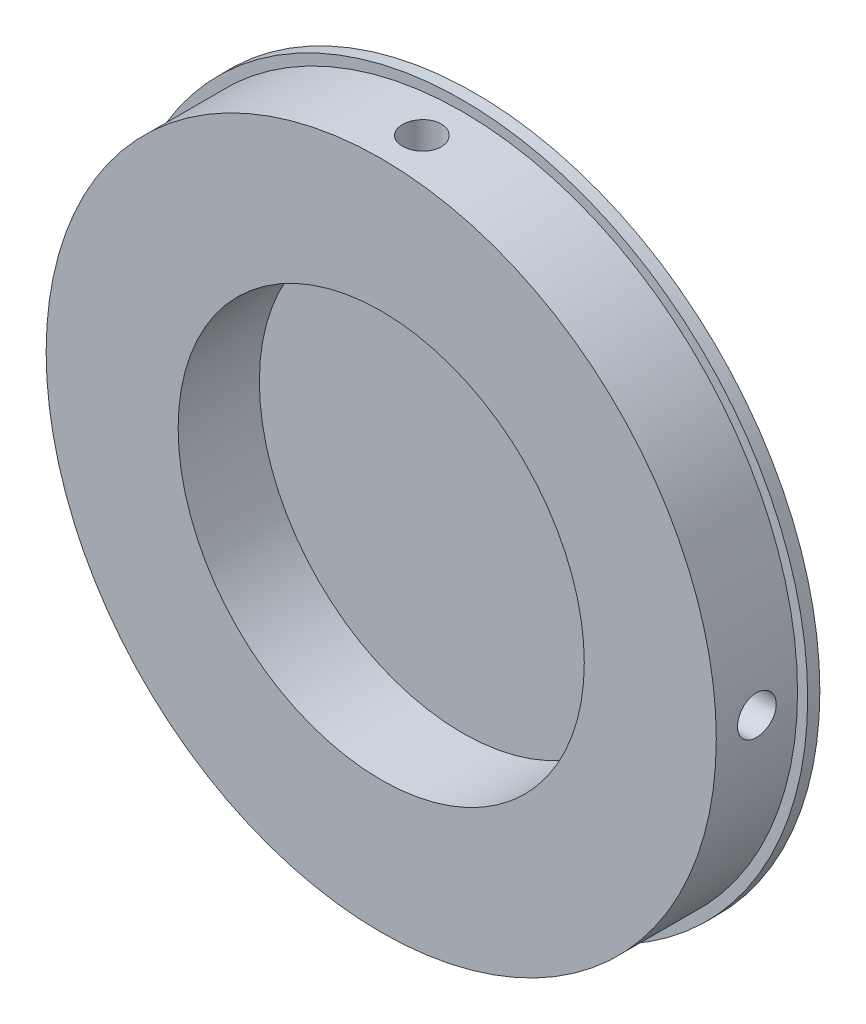
SolidWorks part; units mm, degrees
ref_plane "Front Plane" through (0, 0, 0) normal (0, 0, 1) x (1, 0, 0)
ref_plane "Top Plane" through (0, 0, 0) normal (0, 1, 0) x (1, 0, 0)
ref_plane "Right Plane" through (0, 0, 0) normal (1, 0, 0) x (0, 0, -1)
sketch "Sketch1" plane through (0, 0, 0) normal (0, 0, 1) x (1, 0, 0)
  circle A0 centre (0, 0) radius 85
ref_plane "Plane1" through (0, 0, 3) normal (0, 0, 1) x (1, 0, 0)
sketch "Sketch2" plane through (0, 0, 3) normal (0, 0, 1) x (1, 0, 0)
  circle A0 centre (0, 0) radius 82.5
extrude "Boss-Extrude2" add sketch "Sketch1" along normal blind 3 contours A0
extrude "Boss-Extrude3" add sketch "Sketch2" along normal blind 20 contours A0
ref_plane "Plane2" through (0, 0, 23) normal (0, 0, 1) x (1, 0, 0)
sketch "Sketch3" plane through (0, 0, 23) normal (0, 0, 1) x (1, 0, 0)
  circle A0 centre (0, 0) radius 50
extrude "Cut-Extrude1" cut sketch "Sketch3" against normal blind 20
ref_plane "Plane3" through (0, 82.5, 0) normal (0, -1, 0) x (-1, 0, 0)
sketch "Sketch9" plane through (0, 82.5, 0) normal (0, -1, 0) x (-1, 0, 0)
  line L0 (0, -3) -> (0, -13)
  line L1 (-93.5, -3) -> (93.5, -3) construction
  circle A0 centre (0, -13) radius 4.7625
ref_plane "Plane4" through (0, -82.5, 0) normal (0, 1, 0) x (1, 0, 0)
ref_plane "Plane5" through (82.5, 0, 0) normal (1, 0, 0) x (0, 0, -1)
ref_plane "Plane6" through (-82.5, 0, 0) normal (1, 0, 0) x (0, 0, -1)
extrude "Cut-Extrude9" cut sketch "Sketch9" along normal blind 19.05 contours A0
sketch "Sketch13" plane through (0, -82.5, 0) normal (0, 1, 0) x (1, 0, 0)
  line L0 (0, -3) -> (0, -13)
  line L1 (-82.5, -3) -> (82.5, -3) construction
  circle A0 centre (0, -13) radius 4.7625
sketch "Sketch14" plane through (82.5, 0, 0) normal (1, 0, 0) x (0, 0, -1)
  line L0 (-3, 0) -> (-13, 0)
  line L1 (-3, 82.5) -> (-3, -82.5) construction
  circle A0 centre (-13, 0) radius 4.7625
extrude "Cut-Extrude10" cut sketch "Sketch14" against normal blind 19.05 contours A0
extrude "Cut-Extrude11" cut sketch "Sketch13" along normal blind 19.05 contours A0
sketch "Sketch15" plane through (-82.5, 0, 0) normal (1, 0, 0) x (0, 0, -1)
  line L0 (-3, 0) -> (-13, 0)
  line L1 (-3, 82.5) -> (-3, -82.5) construction
  circle A0 centre (-13, 0) radius 4.7625
extrude "Cut-Extrude12" cut sketch "Sketch15" along normal blind 19.05 contours A0
